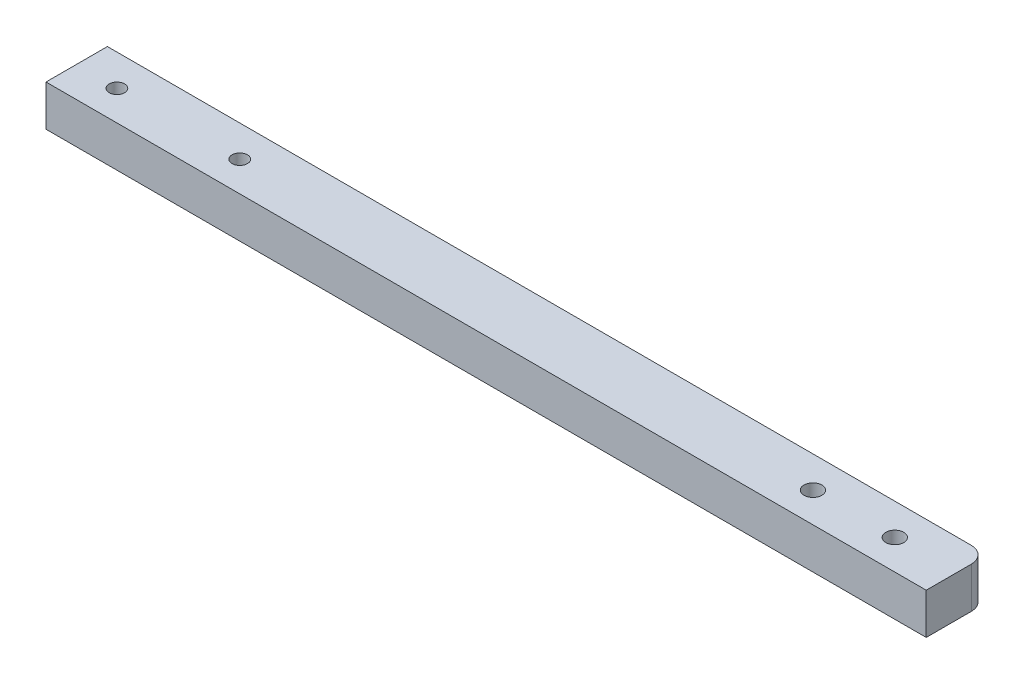
SolidWorks part; units mm, degrees
material "Beech"
ref_plane "Front Plane" through (0, 0, 0) normal (0, 0, 1) x (1, 0, 0)
ref_plane "Top Plane" through (0, 0, 0) normal (0, 1, 0) x (1, 0, 0)
ref_plane "Right Plane" through (0, 0, 0) normal (1, 0, 0) x (0, 0, -1)
sketch "Sketch1" plane through (0, 0, 0) normal (0, 1, 0) x (1, 0, 0)
  line L1 (0, 0) -> (304.8, 0)
  line L2 (0, 0) -> (0, 304.8)
  line L3 (0, 304.8) -> (304.8, 304.8)
  line L4 (304.8, 0) -> (304.8, 304.8)
  dimension "D1" = 304.8
  dimension "D2" = 304.8
extrude "Boss-Extrude1" add sketch "Sketch1" along normal blind 6.35
sketch "Sketch2" plane through (0, 6.35, 0) normal (0, 1, 0) x (1, 0, 0)
  line L1 (304.8, 304.8) -> (0, 304.8) construction
  line L2 (136.525, 304.8) -> (136.525, 295.275)
  line L3 (136.525, 295.275) -> (0, 295.275)
  line L4 (0, 304.8) -> (0, 0) construction
  line L6 (0, 295.275) -> (0, 0)
  line L7 (0, 0) -> (304.8, 0)
  line L8 (304.8, 0) -> (304.8, 304.8)
  line L9 (304.8, 304.8) -> (136.525, 304.8)
  dimension "D1" = 136.525
  dimension "D2" = 9.525
extrude "Cut-Extrude2" cut sketch "Sketch2" against normal blind 6.35 contours L3 L6 L7 L8 L9 L2
sketch "Sketch3" plane through (0, 6.35, 0) normal (0, 1, 0) x (1, 0, 0)
  line L0 (0, 304.8) -> (0, 295.275) construction
  line L1 (136.525, 304.8) -> (136.525, 295.275) construction
  circle A0 centre (6.35, 299.9268) radius 1.1906
  circle A1 centre (25.4, 299.9268) radius 1.1906
  circle A2 centre (114.3, 299.9268) radius 1.3891
  circle A3 centre (127, 299.9268) radius 1.3891
  dimension "D1" = 2.3813
  dimension "D2" = 2.3813
  dimension "D3" = 2.7781
  dimension "D4" = 2.7781
  dimension "D5" = 6.35
  dimension "D6" = 25.4
  dimension "D7" = 9.525
  dimension "D8" = 22.225
extrude "Cut-Extrude3" cut sketch "Sketch3" against normal through all
fillet "Fillet2" radius 2.54 1 edges at (136.525, 3.175, -304.8)
